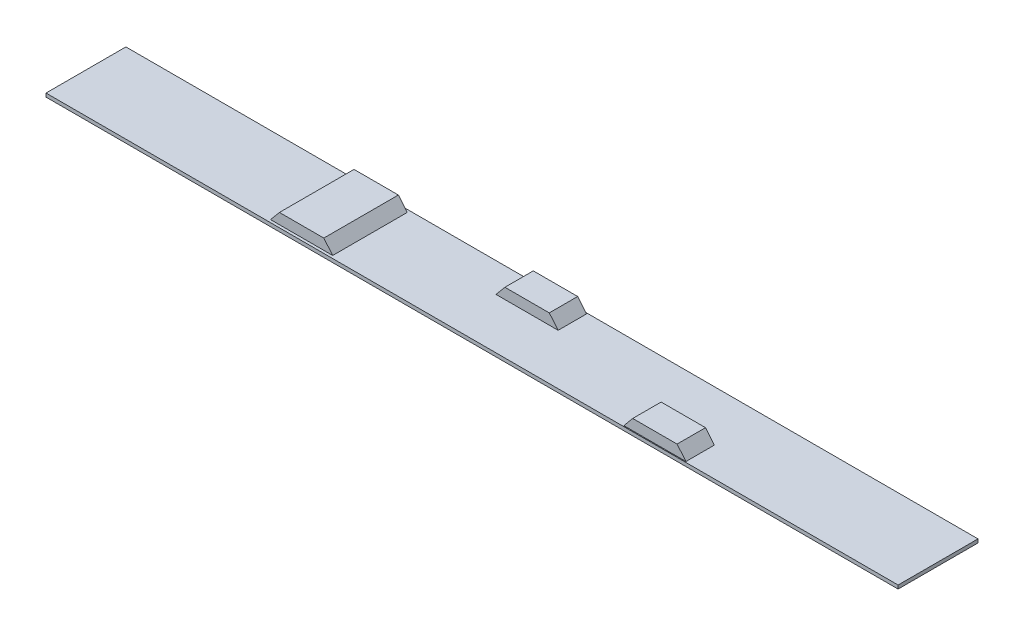
SolidWorks part; units mm, degrees
ref_plane "Front Plane" through (0, 0, 0) normal (0, 0, 1) x (1, 0, 0)
ref_plane "Top Plane" through (0, 0, 0) normal (0, 1, 0) x (1, 0, 0)
ref_plane "Right Plane" through (0, 0, 0) normal (1, 0, 0) x (0, 0, -1)
sketch "Sketch1" plane through (0, 0, 0) normal (0, 1, 0) x (1, 0, 0)
  line L1 (-1200, -112.5) -> (1200, -112.5)
  line L2 (-1200, -112.5) -> (-1200, 112.5)
  line L3 (-1200, 112.5) -> (1200, 112.5)
  line L4 (1200, -112.5) -> (1200, 112.5)
  line L5 (-1200, -112.5) -> (1200, 112.5) construction
  line L6 (-1200, 112.5) -> (1200, -112.5) construction
  point P0 (0, 0)
  dimension "D1" = 2400
  dimension "D2" = 225
extrude "Boss-Extrude1" add sketch "Sketch1" along normal blind 10
sketch "Sketch2" plane through (0, 0, 0) normal (0, 0, 1) x (1, 0, 0)
  line L0 (425, 10) -> (450, 40)
  line L1 (-1200, 10) -> (1200, 10) construction
  line L2 (450, 40) -> (575, 40)
  line L3 (575, 40) -> (600, 10)
  line L4 (425, 10) -> (600, 10)
  point P4 (512.5, 10)
  point P8 (512.5, 40)
  dimension "D1" = 175
  dimension "D2" = 125
  dimension "D3" = 30
  dimension "D4" = 600
extrude "Boss-Extrude2" add sketch "Sketch2" along normal blind 80 from offset 30
sketch "Sketch3" plane through (0, 0, 0) normal (0, 0, 1) x (1, 0, 0)
  line L0 (450, 40) -> (425, 10) construction
  line L1 (575, 40) -> (450, 40) construction
  line L2 (425, 10) -> (600, 10) construction
  line L3 (600, 10) -> (575, 40) construction
  line L4 (600, 10) -> (575, 40) construction
  line L5 (575, 40) -> (450, 40) construction
  line L6 (425, 10) -> (600, 10) construction
  line L7 (450, 40) -> (425, 10) construction
  line L8 (100, 10) -> (75, 40)
  line L9 (75, 40) -> (-50, 40)
  line L10 (-50, 40) -> (-75, 10)
  line L11 (-75, 10) -> (100, 10)
  dimension "D1" = 2
extrude "Boss-Extrude4" add sketch "Sketch3" against normal blind 80 from offset 30 offset against normal yes
sketch "Sketch5" plane through (0, 0, 0) normal (0, 0, 1) x (1, 0, 0)
  line L0 (-550, 40) -> (-575, 10)
  line L1 (-575, 10) -> (-400, 10)
  line L2 (-400, 10) -> (-425, 40)
  line L3 (-425, 40) -> (-550, 40)
  line L4 (-50, 40) -> (-75, 10)
  line L5 (-75, 10) -> (100, 10)
  line L6 (100, 10) -> (75, 40)
  line L7 (75, 40) -> (-50, 40)
  line L8 (-50, 40) -> (-75, 10) construction
  line L9 (-75, 10) -> (100, 10) construction
  line L10 (100, 10) -> (75, 40) construction
  line L11 (75, 40) -> (-50, 40) construction
  dimension "D1" = 0
  dimension "D2" = 2
extrude "Boss-Extrude5" add sketch "Sketch5" along normal blind 105 and the other way blind 105
